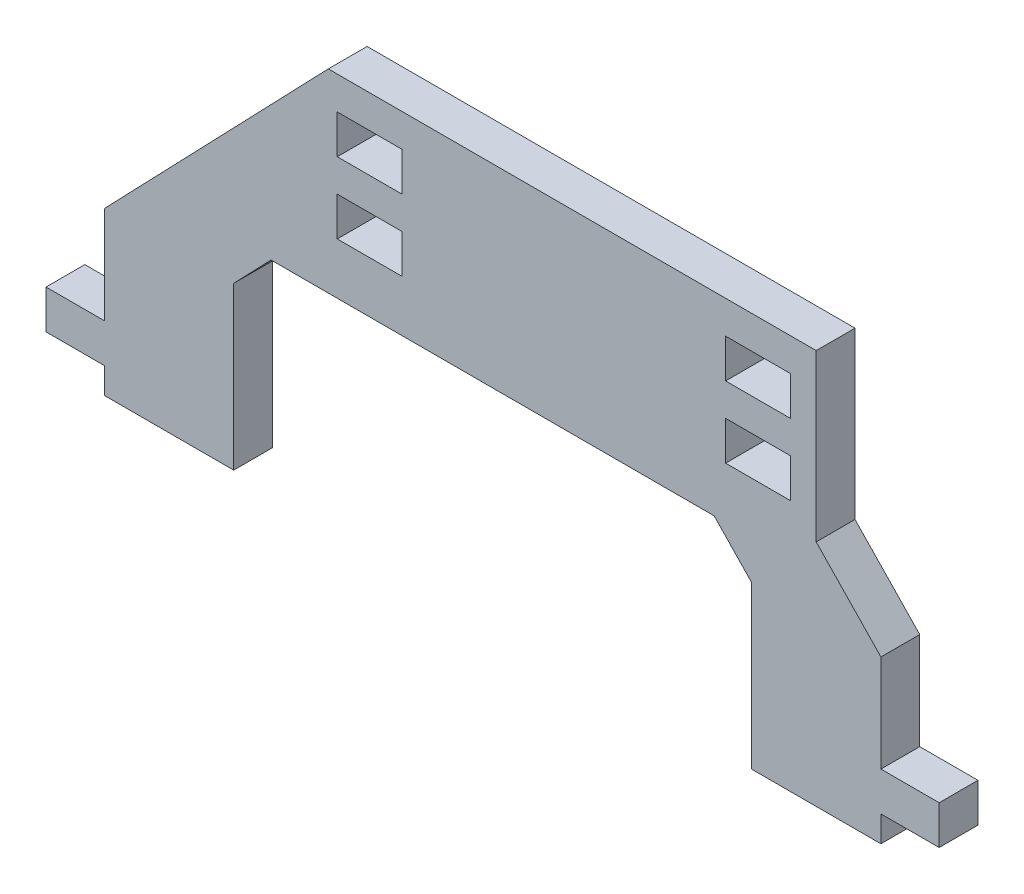
SolidWorks part; units mm, degrees
ref_plane "Front Plane" through (0, 0, 0) normal (0, 0, 1) x (1, 0, 0)
ref_plane "Top Plane" through (0, 0, 0) normal (0, 1, 0) x (1, 0, 0)
ref_plane "Right Plane" through (0, 0, 0) normal (1, 0, 0) x (0, 0, -1)
sketch "Sketch1" plane through (0, 0, 0) normal (0, 0, 1) x (1, 0, 0)
  line L16 (30, -4.25) -> (30, -11.75)
  line L17 (30, -14.75) -> (30, -16.75)
  line L18 (-30, -14.75) -> (-30, -16.75)
  line L20 (20, -16.75) -> (20, -4.25)
  line L23 (30, -16.75) -> (20, -16.75)
  line L24 (25, 0.95) -> (30, -4.25)
  line L25 (20, -4.25) -> (17.1154, -1.25)
  line L27 (-17.1154, -1.25) -> (17.1154, -1.25)
  line L28 (25, 0.95) -> (25, 13.75)
  line L29 (-12.6923, 13.75) -> (25, 13.75)
  line L30 (-20, -4.25) -> (-17.1154, -1.25)
  line L31 (-20, -16.75) -> (-20, -4.25)
  line L32 (-30, -16.75) -> (-20, -16.75)
  line L33 (-30, -4.25) -> (-30, -11.75)
  line L34 (-25, 0.95) -> (-30, -4.25)
  line L40 (-30, -16.75) -> (-30, -14.75) construction
  line L41 (30, -11.75) -> (34.5, -11.75)
  line L42 (-30, -14.75) -> (-34.5, -14.75)
  line L44 (-30, -11.75) -> (-34.5, -11.75)
  line L45 (-34.5, -14.75) -> (-34.5, -11.75)
  line L46 (34.5, -14.75) -> (34.5, -11.75)
  line L47 (30, -14.75) -> (34.5, -14.75)
  line L49 (-25, 0.95) -> (-12.6923, 13.75)
  point P0 (0, 0)
  dimension "D1" = 2
  dimension "D2" = 12.5
  dimension "D3" = 2
  dimension "D4" = 3
  dimension "D5" = 3
  dimension "D6" = 4.5
  dimension "D7" = 15
extrude "Boss-Extrude1" add sketch "Sketch1" along normal blind 3
sketch "Sketch2" plane through (0, 0, 3) normal (0, 0, -1) x (-1, 0, 0)
  line L0 (25, 6.9671) -> (7, 6.9671) construction
  line L2 (7, 8.2171) -> (7, 5.7171) construction
  line L3 (7, 2.7171) -> (12, 2.7171)
  line L4 (7, 8.2171) -> (12, 8.2171)
  line L5 (7, 8.2171) -> (7, 11.2171)
  line L6 (7, 11.2171) -> (12, 11.2171)
  line L7 (12, 8.2171) -> (12, 11.2171)
  line L8 (12, 5.7171) -> (12, 2.7171)
  line L9 (7, 5.7171) -> (12, 5.7171)
  line L10 (7, 5.7171) -> (7, 2.7171)
  line L19 (-23, 2.7171) -> (-18, 2.7171)
  line L20 (-18, 5.7171) -> (-18, 2.7171)
  line L21 (-23, 5.7171) -> (-18, 5.7171)
  line L22 (-23, 5.7171) -> (-23, 2.7171)
  line L23 (-23, 8.2171) -> (-23, 11.2171)
  line L24 (-23, 8.2171) -> (-18, 8.2171)
  line L25 (-18, 8.2171) -> (-18, 11.2171)
  line L26 (-23, 11.2171) -> (-18, 11.2171)
  line L28 (17.5, 10.9671) -> (25, 10.9671) construction
  line L29 (25, 10.9671) -> (25, 6.9671) construction
  point P6 (7, 6.9671)
  dimension "D1" = 18
  dimension "D2" = 2.5
  dimension "D3" = 5
  dimension "D5" = 4
  dimension "D6" = 3
  dimension "D4" = 2
extrude "Cut-Extrude2" cut sketch "Sketch2" along normal blind 3
